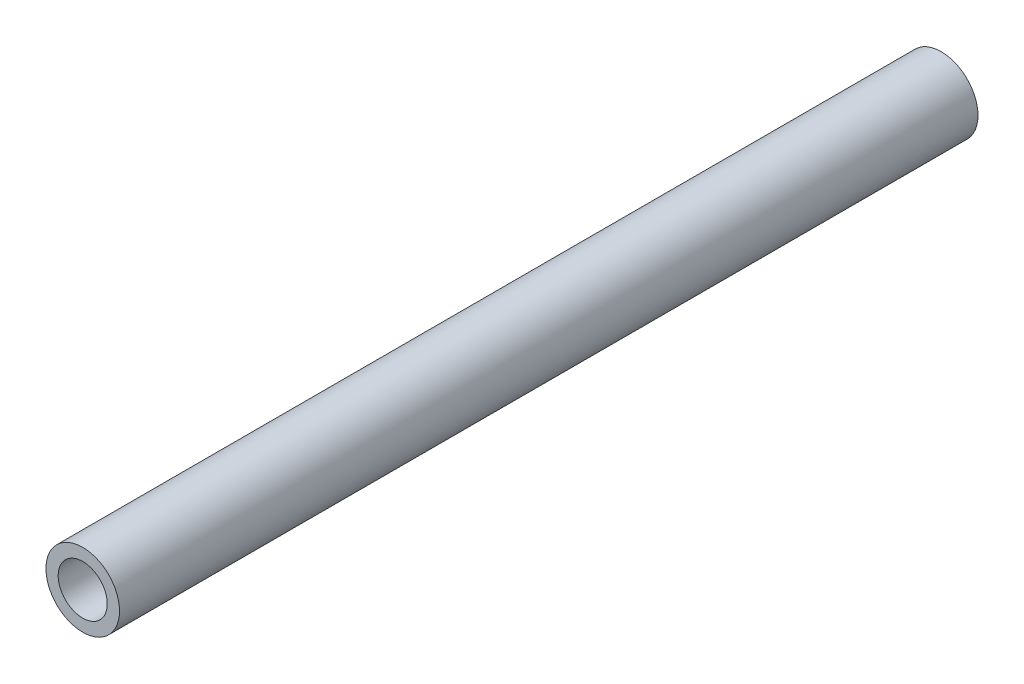
SolidWorks part; units mm, degrees
material "Thornel VCB-20 Carbon Cloth"
ref_plane "Front Plane" through (0, 0, 0) normal (0, 0, 1) x (1, 0, 0)
ref_plane "Top Plane" through (0, 0, 0) normal (0, 1, 0) x (1, 0, 0)
ref_plane "Right Plane" through (0, 0, 0) normal (1, 0, 0) x (0, 0, -1)
sketch "Sketch1" plane through (0, 0, 0) normal (0, 0, 1) x (1, 0, 0)
  circle A0 centre (-0.9922, 0.0115) radius 1.5
  circle A1 centre (-0.9922, 0.0115) radius 1
  dimension "D1" = 3
  dimension "D2" = 2
extrude "Boss-Extrude1" add sketch "Sketch1" along normal blind 35
